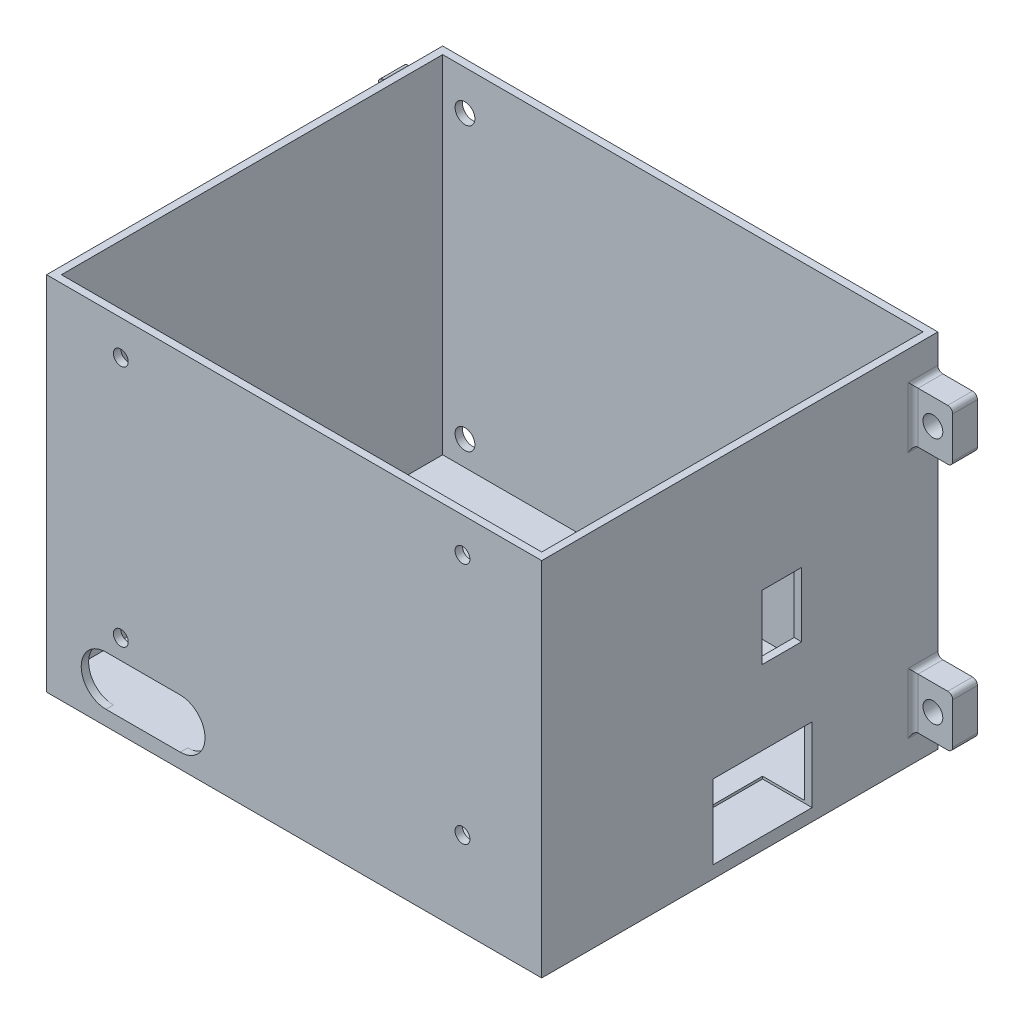
SolidWorks part; units mm, degrees
ref_plane "Front" through (0, 0, 0) normal (0, 0, 1) x (1, 0, 0)
ref_plane "Top" through (0, 0, 0) normal (0, 1, 0) x (1, 0, 0)
ref_plane "Right" through (0, 0, 0) normal (1, 0, 0) x (0, 0, -1)
sketch "Sketch1" plane through (0, 0, 0) normal (0, 1, 0) x (1, 0, 0)
  line L1 (-50, -40) -> (50, -40)
  line L2 (-50, -40) -> (-50, 40)
  line L3 (-50, 40) -> (50, 40)
  line L4 (50, -40) -> (50, 40)
  line L5 (-50, -40) -> (50, 40) construction
  line L6 (-50, 40) -> (50, -40) construction
  point P0 (0, 0)
  dimension "D1" = 100
  dimension "D2" = 80
extrude "Boss-Extrude1" add sketch "Sketch1" along normal blind 3
sketch "Sketch2" plane through (0, 3, 0) normal (0, 1, 0) x (1, 0, 0)
  line L1 (-48.5, -38.5) -> (48.5, -38.5)
  line L2 (-48.5, -38.5) -> (-48.5, 38.5)
  line L3 (-48.5, 38.5) -> (48.5, 38.5)
  line L4 (48.5, -38.5) -> (48.5, 38.5)
  line L5 (-48.5, -38.5) -> (48.5, 38.5) construction
  line L6 (-48.5, 38.5) -> (48.5, -38.5) construction
  line L7 (-50, -40) -> (50, -40)
  line L8 (-50, -40) -> (-50, 40)
  line L9 (-50, 40) -> (50, 40)
  line L10 (50, -40) -> (50, 40)
  line L11 (-50, -40) -> (50, 40) construction
  line L12 (-50, 40) -> (50, -40) construction
  point P0 (0, 0)
  point P6 (0, 0)
  dimension "D1" = 97
  dimension "D2" = 77
extrude "Boss-Extrude2" add sketch "Sketch2" along normal blind 70
sketch "Sketch3" plane through (0, 3, 0) normal (0, 1, 0) x (1, 0, 0)
  line L0 (48.5, 38.5) -> (-48.5, 38.5) construction
  line L1 (-48.5, 38.5) -> (-48.5, -38.5) construction
  circle A0 centre (-38.5, 28.5) radius 1.5
  circle A1 centre (-38.5, -20.5) radius 1.5
  circle A2 centre (19.5, 28.5) radius 1.5
  circle A3 centre (19.5, -20.5) radius 1.5
  dimension "D1" = 3
  dimension "D4" = 2
  dimension "D6" = 3
  dimension "D2" = 10
  dimension "D3" = 10
  dimension "D7" = 49
  dimension "D8" = 0
sketch "Sketch4" plane through (0, 0, 40) normal (0, 0, 1) x (1, 0, 0)
  line L0 (-38, 8) -> (-23, 8) construction
  line L1 (-38, 13) -> (-23, 13)
  line L2 (-38, 3) -> (-23, 3)
  line L3 (-50, 73) -> (-50, 0) construction
  line L4 (-50, 0) -> (50, 0) construction
  arc A0 (-38, 13) -> (-38, 3) centre (-38, 8) ccw
  arc A1 (-23, 3) -> (-23, 13) centre (-23, 8) ccw
  point P2 (-30.5, 8)
  dimension "D1" = 10
  dimension "D2" = 15
  dimension "D3" = 19.5
  dimension "D4" = 8
extrude "Cut-Extrude1" cut sketch "Sketch4" against normal blind 3
sketch "Sketch5" plane through (0, 0, -40) normal (0, 0, -1) x (-1, 0, 0)
  line L0 (50, 5.848) -> (58, 5.848)
  line L1 (-58, 5.848) -> (-50, 5.848)
  line L2 (-58, 5.848) -> (-58, 16.152)
  line L3 (-58, 16.152) -> (-50, 16.152)
  line L4 (-50, 5.848) -> (-50, 16.152)
  line L5 (-58, 5.848) -> (-50, 16.152) construction
  line L6 (-58, 16.152) -> (-50, 5.848) construction
  line L7 (-50, 0) -> (50, 0) construction
  line L8 (50, 5.848) -> (50, 16.152)
  line L9 (50, 16.152) -> (58, 16.152)
  line L10 (58, 5.848) -> (58, 16.152)
  line L11 (50, 5.848) -> (58, 16.152) construction
  line L12 (50, 16.152) -> (58, 5.848) construction
  circle A0 centre (-54, 11) radius 2
  circle A1 centre (54, 11) radius 2
  point P0 (-54, 11)
  point P11 (54, 11)
  dimension "D4" = 4
  dimension "D1" = 11
  dimension "D2" = 54
  dimension "D3" = 8
  dimension "D6" = 10.3041
  dimension "D5" = 2
extrude "Boss-Extrude4" add sketch "Sketch5" against normal blind 5
fillet "Fillet8" radius 1 1 edges at (58, 16.152, -37.5)
fillet "Fillet9" radius 1 2 edges at (58, 5.848, -37.5)
fillet "Fillet10" radius 1 2 edges
fillet "Fillet11" radius 1 2 edges
fillet "Fillet12" radius 1 3 edges at (50.2929, 5.5551, -35) (50.2929, 16.4449, -35) (50, 11, -35)
fillet "Fillet13" radius 1 1 edges at (-58, 5.848, -37.5)
fillet "Fillet14" radius 1 2 edges at (-58, 16.152, -37.5)
fillet "Fillet15" radius 1 3 edges
fillet "Fillet16" radius 1 1 edges
fillet "Fillet17" radius 1 3 edges at (-50.2929, 5.5551, -35) (-50.2929, 16.4449, -35) (-50, 11, -35)
extrude "Cut-Extrude2" cut sketch "Sketch3" against normal blind 10
sketch "Sketch7" plane through (0, 0, 40) normal (0, 0, 1) x (1, 0, 0)
  circle A0 centre (-35, 66) radius 1.5
  circle A1 centre (34, 66) radius 1.5
  circle A2 centre (-35, 17) radius 1.5
  circle A3 centre (34, 17) radius 1.5
  point P2 (-26.6055, 57.087)
  dimension "D1" = 3
  dimension "D2" = 69
  dimension "D3" = 49
  dimension "D4" = 69
  dimension "D5" = 49
  dimension "D6" = 35
  dimension "D7" = 17
extrude "Cut-Extrude4" cut sketch "Sketch7" against normal blind 10
sketch "Sketch8" plane through (0, 0, -40) normal (0, 0, -1) x (-1, 0, 0)
  line L0 (-50, 73) -> (50, 73) construction
  circle A0 centre (-45, 65) radius 2
  circle A1 centre (44, 65) radius 2
  circle A2 centre (-45, 8) radius 2
  circle A3 centre (44, 8) radius 2
  point P0 (-24.993, 32.0926)
  dimension "D1" = 4
  dimension "D2" = 4
  dimension "D3" = 4
  dimension "D4" = 4
  dimension "D5" = 89
  dimension "D6" = 89
  dimension "D7" = 57
  dimension "D8" = 57
  dimension "D9" = 45
  dimension "D11" = 8
  dimension "D10" = 8
extrude "Cut-Extrude5" cut sketch "Sketch8" against normal blind 10
sketch "Sketch9" plane through (50, 0, 0) normal (1, 0, 0) x (0, 0, -1)
  line L1 (-5.4, 2.5) -> (14.6, 2.5)
  line L2 (-5.4, 2.5) -> (-5.4, 17.5)
  line L3 (-5.4, 17.5) -> (14.6, 17.5)
  line L4 (14.6, 2.5) -> (14.6, 17.5)
  line L5 (-5.4, 2.5) -> (14.6, 17.5) construction
  line L6 (-5.4, 17.5) -> (14.6, 2.5) construction
  line L7 (-40, 0) -> (40, 0) construction
  line L8 (40, 73) -> (40, 17.152) construction
  line L11 (4.4752, 32.5604) -> (12.4752, 32.5604)
  line L12 (4.4752, 32.5604) -> (4.4752, 45.5604)
  line L13 (4.4752, 45.5604) -> (12.4752, 45.5604)
  line L14 (12.4752, 32.5604) -> (12.4752, 45.5604)
  point P0 (4.6, 10)
  dimension "D1" = 15
  dimension "D2" = 10
  dimension "D3" = 35.4
  dimension "D4" = 20
  dimension "D5" = 13
  dimension "D6" = 8
extrude "Cut-Extrude7" cut sketch "Sketch9" against normal blind 10
pattern_linear "LPattern1" count 2 spacing 50 along (0, 1, 0) of "Boss-Extrude4", "Fillet8", "Fillet9", "Fillet10", "Fillet11", "Fillet12", "Fillet13", "Fillet14", "Fillet15", "Fillet16", "Fillet17"
